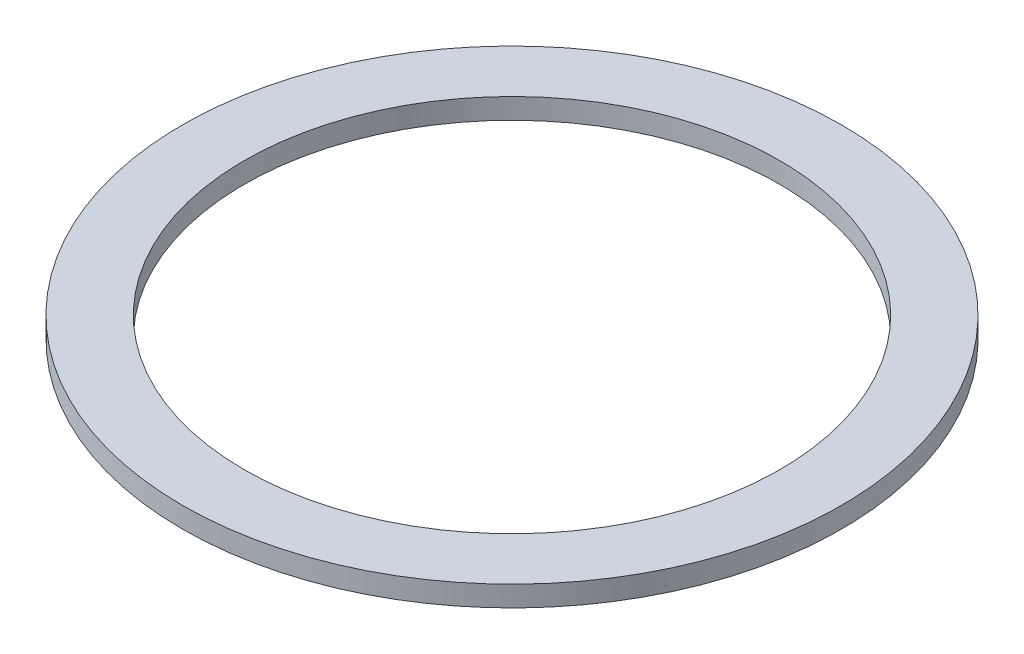
SolidWorks part; units mm, degrees
material "ABS"
ref_plane "Спереди" through (0, 0, 0) normal (0, 0, 1) x (1, 0, 0)
ref_plane "Сверху" through (0, 0, 0) normal (0, 1, 0) x (1, 0, 0)
ref_plane "Справа" through (0, 0, 0) normal (1, 0, 0) x (0, 0, -1)
other "Configuration Table"
sketch "Эскиз1" plane through (0, 0, 0) normal (0, 1, 0) x (1, 0, 0)
  circle A0 centre (0, 0) radius 16
  circle A1 centre (0, 0) radius 13
  dimension "D1" = 32
  dimension "D2" = 26
extrude "Бобышка-Вытянуть1" add sketch "Эскиз1" along normal blind 1
